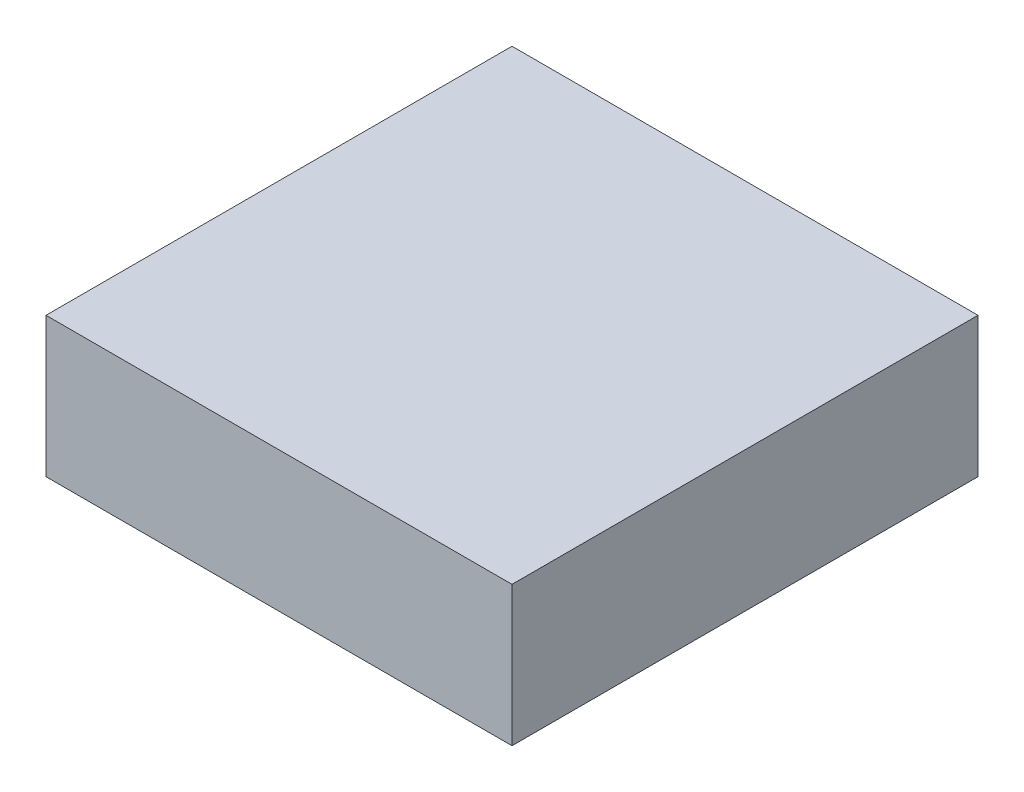
SolidWorks part; units mm, degrees
material "Silicon"
ref_plane "Front Plane" through (0, 0, 0) normal (0, 0, 1) x (1, 0, 0)
ref_plane "Top Plane" through (0, 0, 0) normal (0, 1, 0) x (1, 0, 0)
ref_plane "Right Plane" through (0, 0, 0) normal (1, 0, 0) x (0, 0, -1)
sketch "Sketch1" plane through (0, 0, 0) normal (0, 1, 0) x (1, 0, 0)
  line L1 (-5, 5) -> (5, 5)
  line L2 (-5, 5) -> (-5, -5)
  line L3 (-5, -5) -> (5, -5)
  line L4 (5, 5) -> (5, -5)
  line L5 (-5, 5) -> (5, -5) construction
  line L6 (-5, -5) -> (5, 5) construction
  point P0 (0, 0)
  dimension "D1" = 10
extrude "Boss-Extrude1" add sketch "Sketch1" along normal blind 3
